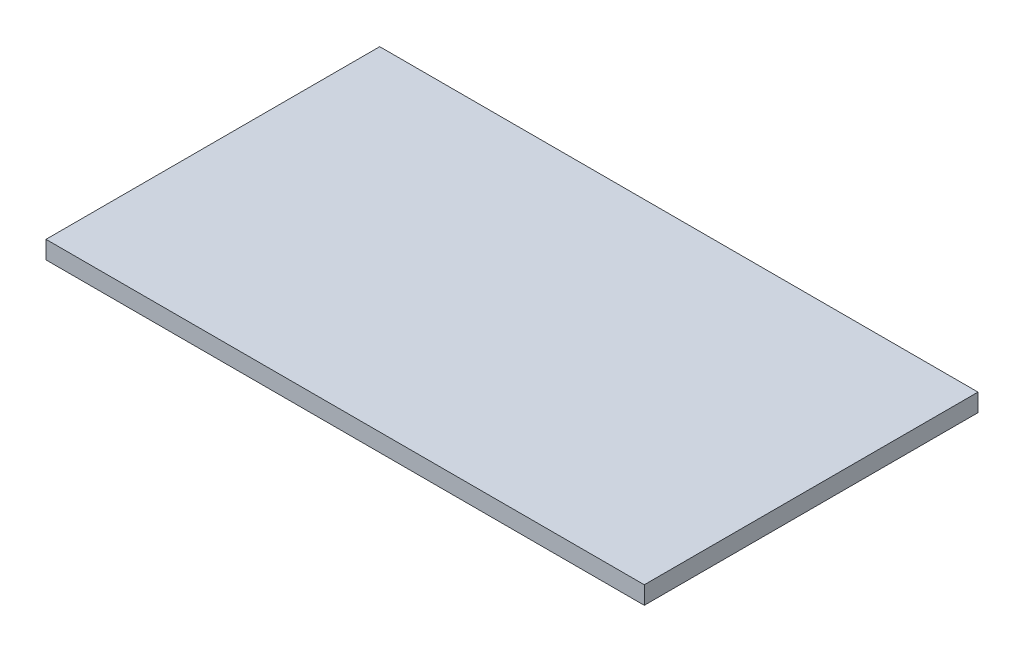
SolidWorks part; units mm, degrees
ref_plane "Front Plane" through (0, 0, 0) normal (0, 0, 1) x (1, 0, 0)
ref_plane "Top Plane" through (0, 0, 0) normal (0, 1, 0) x (1, 0, 0)
ref_plane "Right Plane" through (0, 0, 0) normal (1, 0, 0) x (0, 0, -1)
sketch "Sketch1" plane through (0, 0, 0) normal (0, 1, 0) x (1, 0, 0)
  line L1 (0, 0) -> (1610, 0)
  line L2 (0, 0) -> (0, 898)
  line L3 (0, 898) -> (1610, 898)
  line L4 (1610, 0) -> (1610, 898)
  dimension "D1" = 1610
  dimension "D2" = 898
extrude "Boss-Extrude2" add sketch "Sketch1" along normal blind 48
